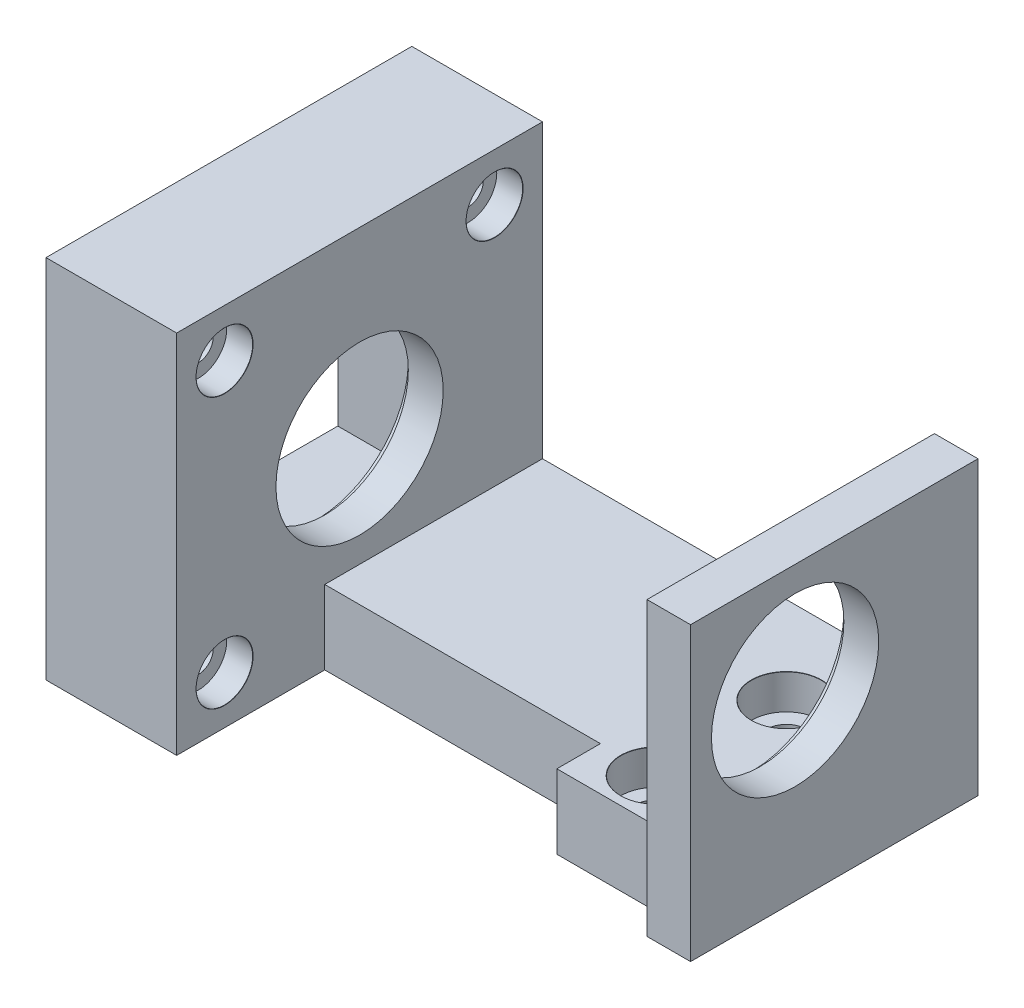
SolidWorks part; units mm, degrees
ref_plane "Front Plane" through (0, 0, 0) normal (0, 0, 1) x (1, 0, 0)
ref_plane "Top Plane" through (0, 0, 0) normal (0, 1, 0) x (1, 0, 0)
ref_plane "Right Plane" through (0, 0, 0) normal (1, 0, 0) x (0, 0, -1)
sketch "Sketch1" plane through (0, 0, 0) normal (0, 1, 0) x (1, 0, 0)
  line L1 (-27.5, -16.5) -> (27.5, -16.5)
  line L2 (-27.5, -16.5) -> (-27.5, 16.5)
  line L3 (-27.5, 16.5) -> (27.5, 16.5)
  line L4 (27.5, -16.5) -> (27.5, 16.5)
  line L5 (-27.5, -16.5) -> (27.5, 16.5) construction
  line L6 (-27.5, 16.5) -> (27.5, -16.5) construction
  point P0 (0, 0)
  dimension "D1" = 33
  dimension "D2" = 55
extrude "Boss-Extrude1" add sketch "Sketch1" along normal blind 5
sketch "Sketch2" plane through (0, 5, 0) normal (0, 1, 0) x (1, 0, 0)
  line L0 (-27.5, -16.5) -> (27.5, -16.5) construction
  line L1 (-27.5, 7.5) -> (-22.5, 7.5)
  line L2 (-27.5, 7.5) -> (-27.5, -16.5)
  line L3 (-27.5, -16.5) -> (-22.5, -16.5)
  line L4 (-22.5, 7.5) -> (-22.5, -16.5)
  line L5 (-27.5, 16.5) -> (-27.5, -16.5) construction
  line L6 (27.5, 7.5) -> (22.5, 7.5)
  line L7 (27.5, 7.5) -> (27.5, -16.5)
  line L8 (27.5, -16.5) -> (22.5, -16.5)
  line L9 (22.5, 7.5) -> (22.5, -16.5)
  line L10 (27.5, -16.5) -> (27.5, 16.5) construction
  dimension "D1" = 5
  dimension "D2" = 5
  dimension "D3" = 24
extrude "Boss-Extrude2" add sketch "Sketch2" along normal blind 25
sketch "Sketch5" plane through (-27.5, 0, 0) normal (1, 0, 0) x (0, 0, -1)
  line L0 (7.5, 30) -> (7.5, 5) construction
  line L3 (-16.5, 30) -> (7.5, 30) construction
  point P0 (-4.5, 17.5)
  point P3 (7.5, 17.5)
  point P12 (-4.5, 30)
hole_wizard "Hole1" positions "Sketch5" profile "Sketch4" legacy
sketch "Sketch4" plane through (-27.5, 17.5, 4.5) normal (0, 1, 0) x (0, 0, 1)
  line L0 (0, 0) -> (0, 5)
  line L1 (0, 5) -> (9.6, 5)
  line L2 (9.6, 5) -> (9.6, 1)
  line L3 (9.6, 1) -> (10.6, 1)
  line L4 (10.6, 1) -> (10.6, 0)
  line L5 (10.6, 0) -> (0, 0)
  line L6 (0, 110) -> (0, -10) construction
  dimension "Diameter" = 19.2
  dimension "Depth" = 5
  dimension "C-Bore Diameter" = 21.2
  dimension "C-Bore Depth" = 1
sketch "Sketch8" plane through (22.5, 0, 0) normal (1, 0, 0) x (0, 0, -1)
  line L1 (-16.5, 30) -> (-16.5, 5) construction
  line L3 (-16.5, 30) -> (7.5, 30) construction
  point P0 (-4.5, 17.5)
  point P8 (-16.5, 17.5)
  point P13 (-4.5, 30)
hole_wizard "Hole2" positions "Sketch8" profile "Sketch7" legacy
sketch "Sketch7" plane through (22.5, 17.5, 4.5) normal (0, 1, 0) x (0, 0, 1)
  line L0 (0, 0) -> (0, 5)
  line L1 (0, 5) -> (9.6, 5)
  line L2 (9.6, 5) -> (9.6, 1)
  line L3 (9.6, 1) -> (10.6, 1)
  line L4 (10.6, 1) -> (10.6, 0)
  line L5 (10.6, 0) -> (0, 0)
  line L6 (0, 110) -> (0, -10) construction
  dimension "Diameter" = 19.2
  dimension "Depth" = 5
  dimension "C-Bore Diameter" = 21.2
  dimension "C-Bore Depth" = 1
sketch "Sketch11" plane through (0, 5, 0) normal (0, 1, 0) x (1, 0, 0)
  line L0 (15.5, 6.5) -> (15.5, -8.5) construction
  line L1 (27.5, -16.5) -> (27.5, 7.5) construction
  line L2 (27.5, 16.5) -> (-22.5, 16.5) construction
  point P0 (15.5, 6.5)
  point P2 (15.5, -8.5)
  dimension "D1" = 15
  dimension "D2" = 12
  dimension "D3" = 10
sketch "Sketch12" plane through (-27.5, 0, 0) normal (-1, 0, 0) x (0, 0, 1)
  line L1 (-16.5, -3.5) -> (25.5, -3.5) construction
  line L2 (-16.5, -3.5) -> (-16.5, 38.5) construction
  line L3 (-16.5, 38.5) -> (25.5, 38.5) construction
  line L4 (25.5, -3.5) -> (25.5, 38.5) construction
  line L5 (-16.5, -3.5) -> (25.5, 38.5) construction
  line L6 (-16.5, 38.5) -> (25.5, -3.5) construction
  line L7 (-16.5, 38.5) -> (25.5, 38.5)
  line L8 (25.5, 38.5) -> (25.5, -3.5)
  line L9 (25.5, -3.5) -> (-16.5, -3.5)
  line L10 (-16.5, -3.5) -> (-16.5, 0)
  line L11 (-16.5, 0) -> (16.5, 0) construction
  line L12 (-16.5, 0) -> (16.5, 0)
  line L13 (16.5, 0) -> (16.5, 30)
  line L14 (16.5, 30) -> (-7.5, 30)
  line L15 (-7.5, 30) -> (-7.5, 5)
  line L16 (-7.5, 5) -> (-16.5, 5)
  line L17 (-16.5, 5) -> (-7.5, 5) construction
  line L18 (-16.5, 5) -> (-16.5, 38.5)
  point P0 (4.5, 17.5)
  dimension "D1" = 42
extrude "Boss-Extrude3" add sketch "Sketch12" against normal up to surface (5 mm away) up to face at (-22.5, 17.5, 14.1)
sketch "Sketch13" plane through (-27.5, 0, 0) normal (-1, 0, 0) x (0, 0, 1)
  line L1 (-16.5, 38.5) -> (25.5, 38.5)
  line L2 (-16.5, 38.5) -> (-16.5, -3.5)
  line L3 (-16.5, -3.5) -> (25.5, -3.5)
  line L4 (25.5, 38.5) -> (25.5, -3.5)
  line L5 (-8, 30) -> (17, 30)
  line L6 (-8, 30) -> (-8, 5)
  line L7 (-8, 5) -> (17, 5)
  line L8 (17, 30) -> (17, 5)
  point P10 (4.5, 30)
  point P11 (4.5, 38.5)
  point P12 (17, 17.5)
  point P13 (25.5, 17.5)
  dimension "D1" = 25
extrude "Boss-Extrude4" add sketch "Sketch13" along normal blind 10
sketch "Sketch18" plane through (-22.5, 0, 0) normal (1, 0, 0) x (0, 0, -1)
  line L2 (-20, 33) -> (11, 33) construction
  line L3 (-20, 33) -> (-20, 2) construction
  line L8 (16.5, 38.5) -> (-25.5, 38.5) construction
  line L9 (-25.5, 38.5) -> (-25.5, -3.5) construction
  point P193 (-20, 33)
  point P335 (-20, 2)
  point P336 (11, 33)
  point P341 (-4.5, 33)
  point P345 (-20, 17.5)
  point P356 (-20, 33)
  point P358 (11, 33)
  point P360 (-20, 2)
  point P367 (-4.5, 38.5)
  point P370 (-25.5, 17.5)
  dimension "D1" = 31
hole_wizard "CBORE for M3 SHCS3" positions "Sketch18" profile "Sketch15" counterbore size "M3" standard "ANSI Metric" end condition through all
sketch "Sketch15" plane through (-22.5, 2, 20) normal (0, 1, 0) x (0, 0, -1)
  line L0 (0, 0) -> (0, 15)
  line L1 (0, 15) -> (1.7, 15)
  line L3 (1.7, 15) -> (1.7, 3)
  line L4 (3.25, 3) -> (1.7, 3)
  line L5 (3.25, 3) -> (3.25, 0.021)
  line L6 (3.25, 0.021) -> (3.275, 0)
  line L7 (3.275, 0) -> (0, 0)
  line L8 (-3.25, 0.021) -> (-3.275, 0) construction
  line L11 (0, -6.35) -> (0, 107.95) construction
  dimension "Thru Hole Dia." = 3.4
  dimension "Thru Hole Depth" = 15
  dimension "C'Bore Dia." = 6.5
  dimension "C'Bore Depth" = 3
  dimension "Near C'Sink Dia." = 6.55
  dimension "Near C'Sink Angle" = 100
sketch "Sketch23" plane through (0, 0, 0) normal (0, -1, 0) x (1, 0, 0)
  line L1 (-22.5, 16.5) -> (27.5, 16.5)
  line L2 (-22.5, 16.5) -> (-22.5, -16.5)
  line L3 (-22.5, -16.5) -> (27.5, -16.5)
  line L4 (27.5, 16.5) -> (27.5, -16.5)
extrude "Boss-Extrude6" add sketch "Sketch23" along normal up to surface (3.5 mm away) up to face at (-30, -3.5, 4.5)
hole_wizard "CBORE for M4 SHCS1" positions "Sketch11" profile "Sketch10" counterbore size "M4" standard "ANSI Metric" end condition through all
sketch "Sketch10" plane through (15.5, 5, -6.5) normal (1, 0, 0) x (0, 0, 1)
  line L0 (0, 0) -> (0, 8.5)
  line L1 (0, 8.5) -> (2.25, 8.5)
  line L3 (2.25, 8.5) -> (2.25, 4)
  line L4 (4, 4) -> (2.25, 4)
  line L5 (4, 4) -> (4, 0.021)
  line L6 (4, 0.021) -> (4.025, 0)
  line L7 (4.025, 0) -> (0, 0)
  line L8 (-4, 0.021) -> (-4.025, 0) construction
  line L11 (0, -6.35) -> (0, 107.95) construction
  dimension "Thru Hole Dia." = 4.5
  dimension "Thru Hole Depth" = 8.5
  dimension "C'Bore Dia." = 8
  dimension "C'Bore Depth" = 4
  dimension "Near C'Sink Dia." = 8.05
  dimension "Near C'Sink Angle" = 100
sketch "Sketch21" plane through (0, 5, 0) normal (0, 1, 0) x (1, 0, 0)
  line L0 (-22.5, -16.5) -> (-22.5, -8.5)
  line L1 (-22.5, 16.5) -> (-22.5, -25.5) construction
  line L2 (-22.5, -16.5) -> (22.5, -16.5) construction
  line L3 (-22.5, -8.5) -> (9.15, -8.5)
  line L4 (9.15, -8.5) -> (9.15, -13.5)
  line L5 (9.15, -13.5) -> (22.5, -13.5)
  line L6 (22.5, 7.5) -> (22.5, -16.5) construction
  line L7 (-22.5, -16.5) -> (22.5, -16.5)
  line L8 (22.5, -16.5) -> (22.5, -13.5)
  circle A0 centre (15.5, -8.5) radius 4.025 construction
  circle A1 centre (15.5, -8.5) radius 4 construction
  dimension "D1" = 5
  dimension "D2" = 6.35
extrude "Cut-Extrude3" cut sketch "Sketch21" against normal through all
sketch "Sketch24" plane through (0, 5, 0) normal (0, 1, 0) x (1, 0, 0)
  line L1 (27.5, 16.5) -> (22.5, 16.5)
  line L2 (27.5, 16.5) -> (27.5, 7.5)
  line L3 (27.5, 7.5) -> (22.5, 7.5)
  line L4 (22.5, 16.5) -> (22.5, 7.5)
extrude "Boss-Extrude7" add sketch "Sketch24" along normal up to surface (25 mm away) up to face at (25, 30, 4.5)
